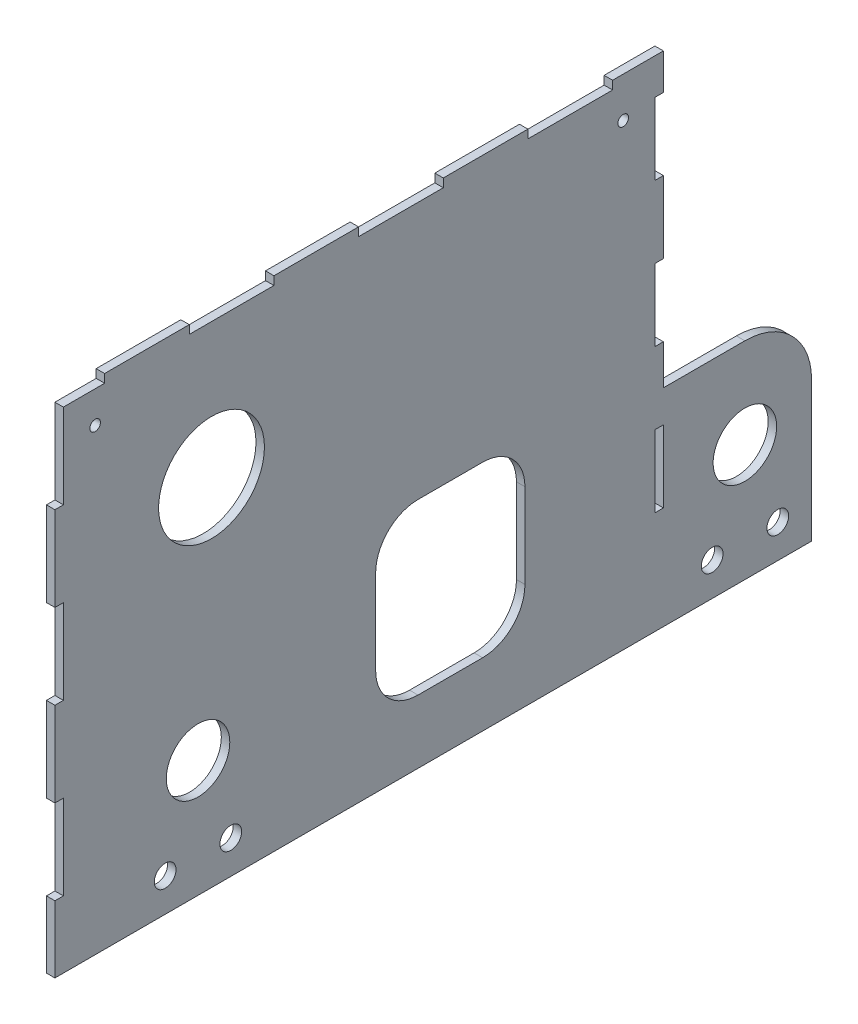
SolidWorks part; units mm, degrees
ref_plane "Front Plane" through (0, 0, 0) normal (0, 0, 1) x (1, 0, 0)
ref_plane "Top Plane" through (0, 0, 0) normal (0, 1, 0) x (1, 0, 0)
ref_plane "Right Plane" through (0, 0, 0) normal (1, 0, 0) x (0, 0, -1)
sketch "Sketch1" plane through (0, 0, 0) normal (1, 0, 0) x (0, 0, -1)
  line L1 (-112.2312, 74.803) -> (112.2312, 74.803)
  line L2 (-112.2312, 74.803) -> (-112.2312, -74.803)
  line L3 (-112.2312, -74.803) -> (112.2312, -74.803)
  line L4 (112.2312, 74.803) -> (112.2312, -74.803)
  line L5 (0, -74.803) -> (0, 74.803) construction
  line L6 (-112.2312, 0) -> (112.2312, 0) construction
  point P0 (0, 0)
  dimension "D1" = 224.4623
  dimension "D2" = 149.606
extrude "Boss-Extrude1" add sketch "Sketch1" along normal blind 2.54
sketch "Sketch2" plane through (2.54, 0, 0) normal (1, 0, 0) x (0, 0, -1)
  line L0 (-112.2312, -74.803) -> (112.2312, -74.803) construction
  line L1 (112.2312, 74.803) -> (67.7812, 74.803)
  line L2 (112.2312, 74.803) -> (112.2312, -12.7381)
  line L3 (112.2312, -12.7381) -> (67.7812, -12.7381)
  line L4 (67.7812, 74.803) -> (67.7812, -12.7381)
  dimension "D1" = 44.45
  dimension "D2" = 62.0649
extrude "Cut-Extrude1" cut sketch "Sketch2" against normal through all
fillet "Fillet1" radius 20.0025 1 edges at (1.27, -12.7381, -112.2312)
hole_wizard "1/4 Clearance Hole1" positions "Sketch3" profile "Sketch5" hole size "1/4" standard "ANSI Inch"
sketch "Sketch3" plane through (2.54, 0, 0) normal (1, 0, 0) x (0, 0, -1)
  line L0 (-112.2312, -74.803) -> (112.2312, -74.803) construction
  line L3 (82.4116, -64.77) -> (102.0966, -64.77) construction
  line L6 (112.2312, -74.803) -> (112.2312, -32.7406) construction
  point P0 (-81.6978, -64.77)
  point P2 (-62.0128, -64.77)
  point P4 (102.0966, -64.77)
  point P6 (82.4116, -64.77)
  dimension "D1" = 10.033
  dimension "D2" = 19.685
  dimension "D3" = 19.685
  dimension "D4" = 144.4244
  dimension "D5" = 10.1346
sketch "Sketch5" plane through (2.54, -64.77, 81.6978) normal (0, 1, 0) x (0, 0, -1)
  line L0 (0, 0) -> (0, 11.3591)
  line L1 (0, 11.3591) -> (3.2639, 9.398)
  line L2 (3.2639, 9.398) -> (3.2639, 0)
  line L5 (3.2639, 0) -> (0, 0)
  line L10 (0, 11.3591) -> (-3.2639, 9.398) construction
  line L11 (0, -6.35) -> (0, 107.95) construction
  dimension "Hole Dia." = 6.5278
  dimension "Hole Depth" = 9.398
  dimension "Drill Angle" = 118
sketch "Sketch6" plane through (2.54, 0, 0) normal (1, 0, 0) x (0, 0, -1)
  line L0 (67.7812, 74.803) -> (-112.2312, 74.803) construction
  line L1 (52.5412, 74.803) -> (27.1412, 74.803)
  line L2 (52.5412, 74.803) -> (52.5412, 72.263)
  line L3 (52.5412, 72.263) -> (27.1412, 72.263)
  line L4 (27.1412, 74.803) -> (27.1412, 72.263)
  line L7 (67.7812, 74.803) -> (67.7812, -12.7381) construction
  dimension "D1" = 2.54
  dimension "D2" = 25.4
  dimension "D3" = 15.24
extrude "Cut-Extrude2" cut sketch "Sketch6" against normal through all
pattern_linear "LPattern1" count 4 spacing 50.8 along (0, 0, 1) of "Cut-Extrude2"
sketch "Sketch7" plane through (2.54, 0, 0) normal (1, 0, 0) x (0, 0, -1)
  line L0 (67.7812, 74.803) -> (67.7812, -12.7381) construction
  line L1 (67.7812, 64.008) -> (65.2412, 64.008)
  line L2 (67.7812, 64.008) -> (67.7812, 42.418)
  line L3 (67.7812, 42.418) -> (65.2412, 42.418)
  line L4 (65.2412, 64.008) -> (65.2412, 42.418)
  line L5 (67.7812, 74.803) -> (52.5412, 74.803) construction
  dimension "D1" = 2.54
  dimension "D2" = 21.59
  dimension "D3" = 10.795
extrude "Cut-Extrude3" cut sketch "Sketch7" against normal through all
pattern_linear "LPattern2" count 3 spacing 43.18 along (0, -1, 0) of "Cut-Extrude3"
sketch "Sketch8" plane through (2.54, 0, 0) normal (1, 0, 0) x (0, 0, -1)
  line L0 (112.2312, -74.803) -> (112.2312, -32.7406) construction
  line L1 (-112.2312, -74.803) -> (112.2312, -74.803) construction
  circle A0 centre (92.2287, -39.737) radius 9.525
  circle A1 centre (-71.8299, -39.737) radius 9.525
  dimension "D1" = 20.0025
  dimension "D2" = 35.066
  dimension "D3" = 19.05
  dimension "D4" = 164.0586
extrude "Cut-Extrude4" cut sketch "Sketch8" against normal through all
sketch "Sketch9" plane through (2.54, 0, 0) normal (1, 0, 0) x (0, 0, -1)
  line L1 (-18.5407, -55.753) -> (26.2395, -55.753)
  line L2 (-18.5407, -55.753) -> (-18.5407, -4.953)
  line L3 (-18.5407, -4.953) -> (26.2395, -4.953)
  line L4 (26.2395, -55.753) -> (26.2395, -4.953)
  line L5 (-112.2312, 72.263) -> (-112.2312, -74.803) construction
  line L6 (-112.2312, -74.803) -> (112.2312, -74.803) construction
  line L7 (-112.2312, 72.263) -> (-99.8588, 72.263) construction
  circle A0 centre (-67.7863, 31.7373) radius 15.875
  dimension "D5" = 44.4449
  dimension "D6" = 31.75
  dimension "D1" = 50.8
  dimension "D2" = 44.7802
  dimension "D3" = 93.6904
  dimension "D4" = 19.05
  dimension "D7" = 40.5257
extrude "Cut-Extrude5" cut sketch "Sketch9" against normal through all
fillet "Fillet2" radius 12.7 4 edges at (1.27, -4.953, -26.2395) (1.27, -4.953, 18.5407) (1.27, -55.753, 18.5407) (1.27, -55.753, -26.2395)
hole_wizard "Tap Drill for M2x0.4 Tap1" [suppressed] positions "Sketch10" profile "Sketch11" hole size "M2x0.4" standard "ANSI Metric"
sketch "Sketch10" plane through (2.54, 0, 0) normal (1, 0, 0) x (0, 0, -1)
  point P0 (-60.8263, 62.1794)
  point P2 (-60.8263, 13.1794)
  point P4 (-2.8263, 13.1794)
  point P6 (-2.8263, 62.1794)
  dimension "D1" = 58
  dimension "D2" = 49
  dimension "D3" = 2.8263
  dimension "D4" = 13.1794
sketch "Sketch11" plane through (2.54, 62.1794, 60.8263) normal (0, 1, 0) x (0, 0, -1)
  line L0 (0, 0) -> (0, 2.54)
  line L1 (0, 2.54) -> (0.8, 2.54)
  line L2 (0.8, 2.54) -> (0.8, 0)
  line L5 (0.8, 0) -> (0, 0)
  line L11 (0, -6.35) -> (0, 107.95) construction
  dimension "Thru Hole Dia." = 1.6
  dimension "Thru Hole Depth" = 2.54
sketch "Sketch12" [suppressed] plane through (2.54, 0, 0) normal (1, 0, 0) x (0, 0, -1)
  line L2 (-5.2438, 0.3175) -> (58.2562, 0.3175)
  line L10 (58.2562, -20.0025) -> (58.2562, 0.3175)
  line L12 (-5.2438, 0.3175) -> (-5.2438, -20.0025)
  line L14 (58.2562, -20.0025) -> (-5.2438, -20.0025)
  line L15 (67.7812, -0.762) -> (67.7812, -12.7381) construction
  line L16 (-112.2312, -74.803) -> (112.2312, -74.803) construction
  dimension "D1" = 9.525
  dimension "D2" = 63.5
  dimension "D3" = 54.8005
  dimension "D5" = 20.32
extrude "Cut-Extrude6" [suppressed] cut sketch "Sketch12" against normal through all
fillet "Fillet3" [suppressed] radius 12.7
fillet "Fillet4" [suppressed] radius 5.08
hole_wizard "M3 Clearance Hole1" positions "Sketch13" profile "Sketch14" hole size "M3" standard "ANSI Metric"
sketch "Sketch13" plane through (2.54, 0, 0) normal (1, 0, 0) x (0, 0, -1)
  line L0 (-112.2312, 72.263) -> (-112.2312, -74.803) construction
  line L1 (-112.2312, 72.263) -> (-99.8588, 72.263) construction
  line L2 (65.2412, 64.008) -> (65.2412, 42.418) construction
  line L3 (27.1412, 72.263) -> (52.5412, 72.263) construction
  point P0 (-102.7062, 62.738)
  point P2 (55.7162, 62.738)
  dimension "D1" = 9.525
  dimension "D2" = 9.525
  dimension "D3" = 9.525
  dimension "D4" = 9.525
sketch "Sketch14" plane through (2.54, 62.738, 102.7062) normal (0, 1, 0) x (0, 0, -1)
  line L0 (0, 0) -> (0, 10.3594)
  line L1 (0, 10.3594) -> (1.6, 9.398)
  line L2 (1.6, 9.398) -> (1.6, 0)
  line L5 (1.6, 0) -> (0, 0)
  line L10 (0, 10.3594) -> (-1.6, 9.398) construction
  line L11 (0, -6.35) -> (0, 107.95) construction
  dimension "Hole Dia." = 3.2
  dimension "Hole Depth" = 9.398
  dimension "Drill Angle" = 118
sketch "Sketch16" plane through (2.54, 0, 0) normal (1, 0, 0) x (0, 0, -1)
  line L0 (-112.2312, 72.263) -> (-112.2312, -74.803) construction
  line L1 (-112.2312, 46.863) -> (-114.7712, 46.863)
  line L2 (-112.2312, 46.863) -> (-112.2312, 21.463)
  line L3 (-112.2312, 21.463) -> (-114.7712, 21.463)
  line L4 (-114.7712, 46.863) -> (-114.7712, 21.463)
  line L5 (-112.2312, 72.263) -> (-99.8588, 72.263) construction
  dimension "D1" = 2.54
  dimension "D2" = 25.4
  dimension "D3" = 25.4
extrude "Boss-Extrude2" add sketch "Sketch16" against normal blind 2.54
pattern_linear "LPattern3" count 3 spacing 50.8 along (0, -1, 0) of "Boss-Extrude2"
sketch "Sketch18" plane through (2.54, 0, 0) normal (1, 0, 0) x (0, 0, -1)
  line L0 (-112.2312, -74.803) -> (112.2312, -74.803) construction
  line L1 (-112.2312, -80.137) -> (-114.7712, -80.137)
  line L2 (-112.2312, -80.137) -> (-112.2312, -74.803)
  line L3 (-112.2312, -74.803) -> (-114.7712, -74.803)
  line L4 (-114.7712, -80.137) -> (-114.7712, -74.803)
  line L5 (-114.7712, -54.737) -> (-114.7712, -80.137) construction
extrude "Cut-Extrude7" cut sketch "Sketch18" against normal through all
